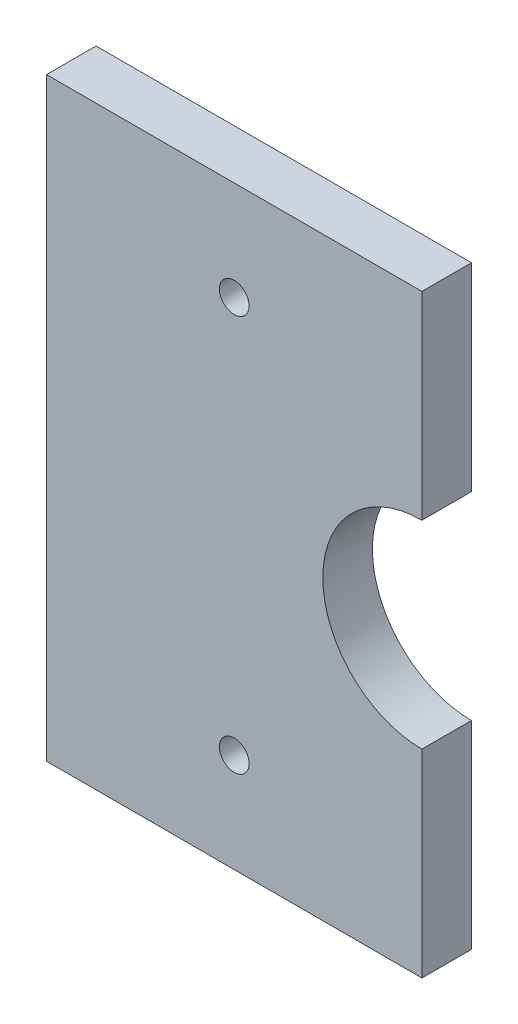
SolidWorks part; units mm, degrees
ref_plane "前视基准面" through (0, 0, 0) normal (0, 0, 1) x (1, 0, 0)
ref_plane "上视基准面" through (0, 0, 0) normal (0, 1, 0) x (1, 0, 0)
ref_plane "右视基准面" through (0, 0, 0) normal (1, 0, 0) x (0, 0, -1)
sketch "草图1" plane through (0, 0, 0) normal (0, 0, 1) x (1, 0, 0)
  line L0 (0, 37.8804) -> (0, -37.8804)
  line L2 (-75.7608, 60) -> (0, 60)
  line L3 (-75.7608, 60) -> (-75.7608, -60)
  line L4 (-75.7608, -60) -> (0, -60)
  line L5 (0, 60) -> (0, -60)
  line L6 (-75.7608, 60) -> (0, -60) construction
  line L7 (-75.7608, -60) -> (0, 60) construction
  circle A0 centre (0, 0) radius 37.8804
  circle A1 centre (-37.8804, 40) radius 3
  circle A2 centre (-37.8804, -40) radius 3
  point P5 (-37.8804, 0)
  dimension "D1" = 120
  dimension "D2" = 80
  dimension "D3" = 40
extrude "凸台-拉伸1" add sketch "草图1" along normal blind 10 contours L0 A0 | A0 L5 L2 L3 L4 A2 A1
sketch "草图5" plane through (0, 0, 10) normal (0, 0, 1) x (1, 0, 0)
  circle A0 centre (0, 0) radius 20
extrude "切除-拉伸1" cut sketch "草图5" against normal blind 20
